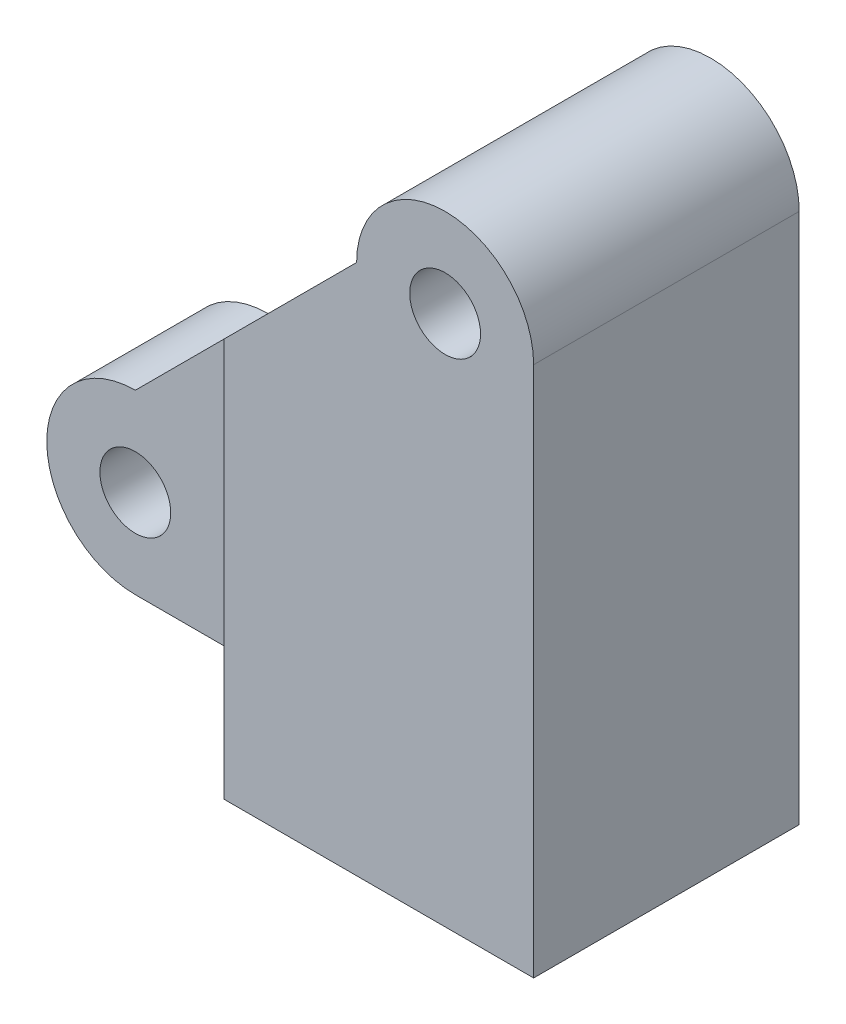
SolidWorks part; units mm, degrees
material "Dökme Alaşımlı Çelik"
ref_plane "Ön Düzlem" through (0, 0, 0) normal (0, 0, 1) x (1, 0, 0)
ref_plane "Üst Düzlem" through (0, 0, 0) normal (0, 1, 0) x (1, 0, 0)
ref_plane "Sağ Düzlem" through (0, 0, 0) normal (1, 0, 0) x (0, 0, -1)
sketch "Sketch1" plane through (0, 0, 0) normal (0, 0, 1) x (1, 0, 0)
  line L0 (0, 0) -> (50, 0) construction
  line L1 (50, 0) -> (50, 50) construction
  line L2 (50, 50) -> (0, 0) construction
  line L3 (0, -10) -> (60, -10)
  line L4 (60, -10) -> (60, 50)
  line L5 (40, 50) -> (0, 10)
  arc A0 (0, 10) -> (0, -10) centre (0, 0) ccw
  arc A1 (60, 50) -> (40, 50) centre (50, 50) ccw
  circle A2 centre (50, 50) radius 4
  circle A3 centre (0, 0) radius 4
  dimension "D3" = 10
  dimension "D4" = 10
  dimension "D1" = 50
  dimension "D2" = 50
extrude "Boss-Extrude1" add sketch "Sketch1" along normal blind 30
sketch "Sketch3" plane through (0, 0, 30) normal (0, 0, 1) x (1, 0, 0)
  line L0 (60, -10) -> (25, -10) construction
  line L1 (0, -10) -> (60, -10) construction
  line L2 (60, -10) -> (25, -10)
  line L3 (25, -10) -> (25, 35)
  line L4 (40, 50) -> (0, 10) construction
  line L5 (60, -10) -> (60, 50) construction
  line L6 (0, -10) -> (60, -10)
  line L7 (40, 50) -> (0, 10)
  line L8 (60, -10) -> (60, 50)
  arc A0 (60, 50) -> (40, 50) centre (50, 50) ccw construction
  arc A1 (60, 50) -> (40, 50) centre (50, 50) ccw
  arc A2 (0, 10) -> (0, -10) centre (0, 0) ccw construction
  arc A3 (0, 10) -> (0, -10) centre (0, 0) ccw
  dimension "D1" = 35
extrude "Cut-Extrude3" cut sketch "Sketch3" against normal blind 15 contours L2 L3 L5 L1 L7
scale "Echelle1" scale about centroid uniform scaling yes scale factor 0.6
